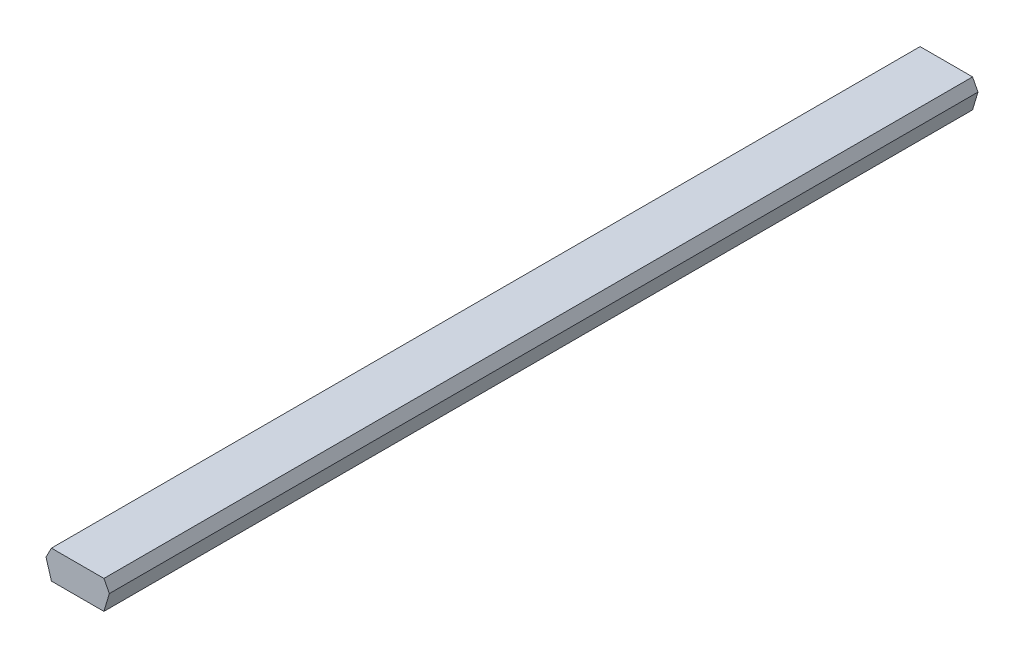
SolidWorks part; units mm, degrees
ref_plane "Front Plane" through (0, 0, 0) normal (0, 0, 1) x (1, 0, 0)
ref_plane "Top Plane" through (0, 0, 0) normal (0, 1, 0) x (1, 0, 0)
ref_plane "Right Plane" through (0, 0, 0) normal (1, 0, 0) x (0, 0, -1)
sketch "Sketch1" plane through (0, 0, 0) normal (0, 0, 1) x (1, 0, 0)
  line L0 (-36.83, -20.066) -> (-44.45, 5.4196)
  line L1 (-44.45, -20.066) -> (44.45, -20.066) construction
  line L2 (-44.45, -20.066) -> (-44.45, 20.066) construction
  line L3 (-44.45, 20.066) -> (44.45, 20.066) construction
  line L4 (44.45, -20.066) -> (44.45, 20.066) construction
  line L5 (-44.45, -20.066) -> (44.45, 20.066) construction
  line L6 (-44.45, 20.066) -> (44.45, -20.066) construction
  line L7 (-36.83, -20.066) -> (36.83, -20.066)
  line L8 (-36.83, -20.066) -> (-36.83, 20.066) construction
  line L9 (-36.83, 20.066) -> (36.83, 20.066)
  line L10 (36.83, -20.066) -> (36.83, 20.066) construction
  line L11 (-36.83, -20.066) -> (36.83, 20.066) construction
  line L12 (-36.83, 20.066) -> (36.83, -20.066) construction
  line L13 (-44.45, 5.4196) -> (-36.83, 20.066)
  line L14 (36.83, 20.066) -> (44.45, 5.4196)
  line L15 (44.45, 5.4196) -> (36.83, -20.066)
  point P0 (0, 0)
  point P6 (0, 0)
  point P11 (0, 0)
  dimension "D1" = 88.9
  dimension "D2" = 40.132
  dimension "D3" = 7.62
  dimension "D4" = 16.51
extrude "Boss-Extrude1" add sketch "Sketch1" along normal blind 1219.2
